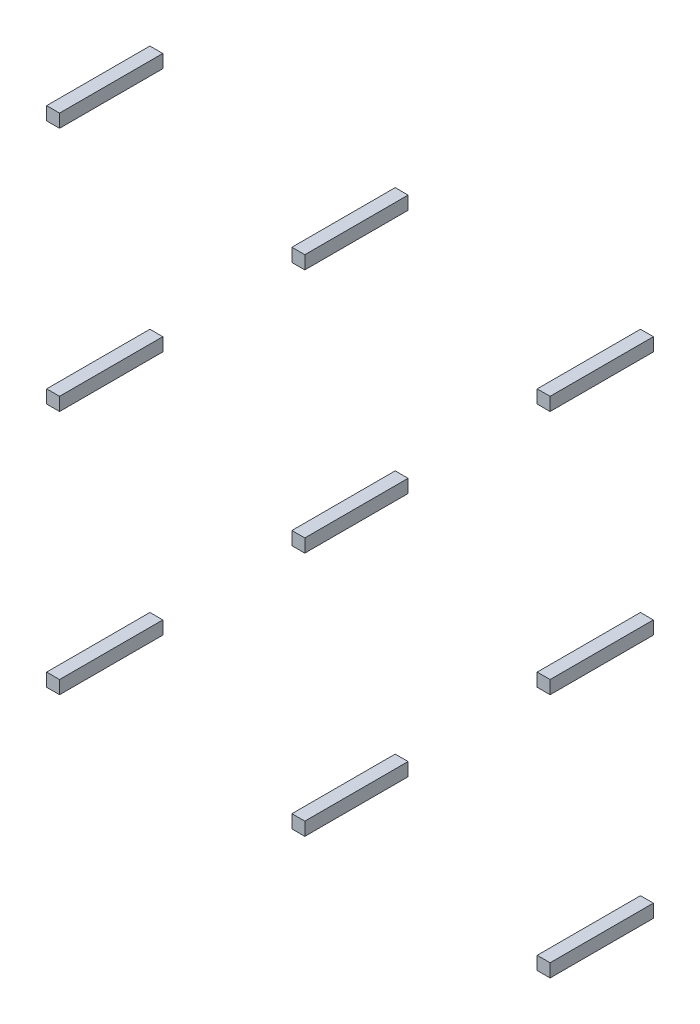
SolidWorks part; units mm, degrees
ref_plane "Front Plane" through (0, 0, 0) normal (0, 0, 1) x (1, 0, 0)
ref_plane "Top Plane" through (0, 0, 0) normal (0, 1, 0) x (1, 0, 0)
ref_plane "Right Plane" through (0, 0, 0) normal (1, 0, 0) x (0, 0, -1)
sketch "Sketch1" plane through (0, 0, 0) normal (0, 0, 1) x (1, 0, 0)
  line L0 (10, -8) -> (10, -9.5) construction
  line L1 (9.5, -9.5) -> (10, -9.5)
  line L2 (9.5, -9.5) -> (9.5, -8.9884)
  line L3 (9.5, -8.9884) -> (10, -8.9884)
  line L4 (10, -9.5) -> (10, -8.9884)
  point P7 (0, 0)
extrude "Boss-Extrude1" add sketch "Sketch1" along normal blind 4
sketch "Sketch2" plane through (0, 0, 0) normal (0, 0, 1) x (1, 0, 0)
  line L0 (9.5, -9.5) -> (11.5, -9.5) construction
  line L1 (11.5, -9.5) -> (10.4047, -9.5) construction
  line L2 (9.5, -9.5) -> (9.5, -7.5) construction
  dimension "D1" = 2
  dimension "D2" = 2
pattern_linear "LPattern3" count 3 spacing 9.5 along (-1, 0, 0) count 3 spacing 9.5 along (0, 1, 0) of "Boss-Extrude1"
